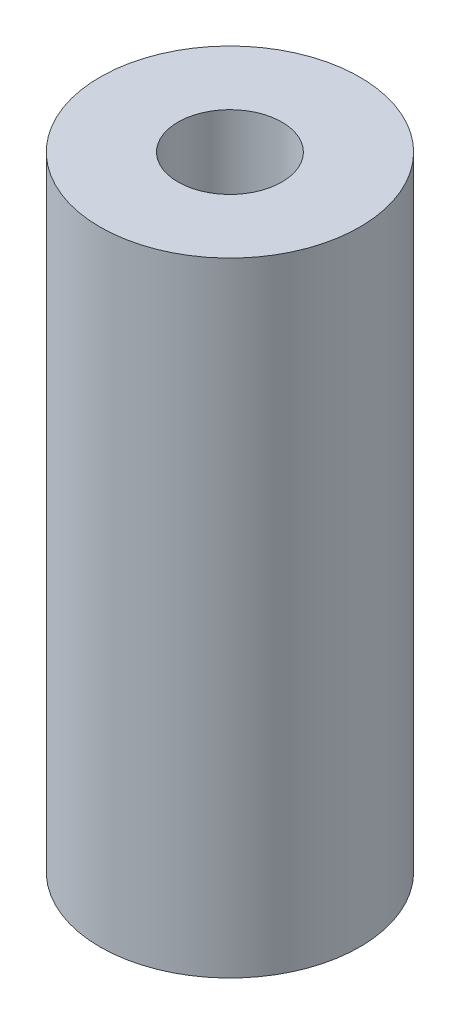
SolidWorks part; units mm, degrees
ref_plane "Ön Düzlem" through (0, 0, 0) normal (0, 0, 1) x (1, 0, 0)
ref_plane "Üst Düzlem" through (0, 0, 0) normal (0, 1, 0) x (1, 0, 0)
ref_plane "Sağ Düzlem" through (0, 0, 0) normal (1, 0, 0) x (0, 0, -1)
sketch "Sketch2" plane through (0, 0, 0) normal (0, 0, 1) x (1, 0, 0)
  line L0 (0, 10.8397) -> (0, 0) construction
  line L1 (3, 0) -> (3, 18)
  line L2 (3, 18) -> (2, 18)
  line L3 (2, 18) -> (2, 24)
  line L4 (2, 24) -> (5, 24)
  line L5 (5, 24) -> (5, 0)
  line L6 (5, 0) -> (3, 0)
  dimension "D1" = 6
  dimension "D2" = 4
  dimension "D3" = 18
  dimension "D4" = 6
  dimension "D5" = 5
revolve "Revolve1" add sketch "Sketch2" angle 360 about L0
sketch "Sketch3" plane through (0, 18, 0) normal (0, -1, 0) x (1, 0, 0)
  circle A0 centre (0, 0) radius 3
  circle A1 centre (0, 0) radius 1
  dimension "D1" = 2
extrude "Boss-Extrude1" add sketch "Sketch3" along normal blind 5
